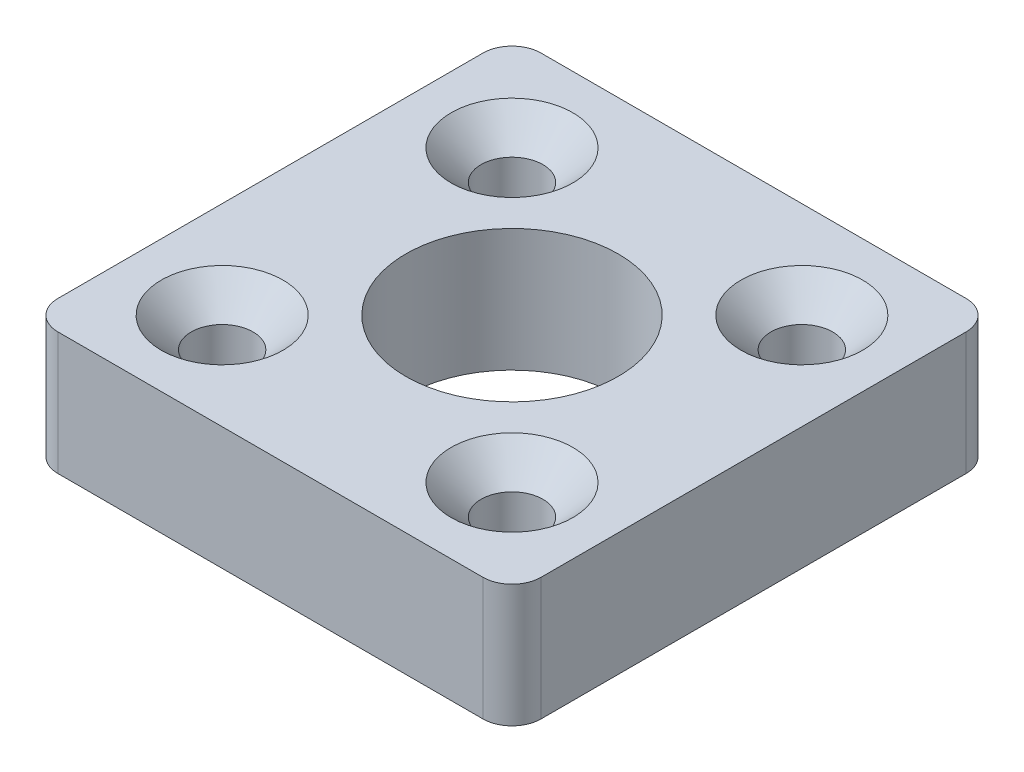
SolidWorks part; units mm, degrees
material "6061 Alloy"
ref_plane "Front Plane" through (0, 0, 0) normal (0, 0, 1) x (1, 0, 0)
ref_plane "Top Plane" through (0, 0, 0) normal (0, 1, 0) x (1, 0, 0)
ref_plane "Right Plane" through (0, 0, 0) normal (1, 0, 0) x (0, 0, -1)
sketch "Sketch2" plane through (0, 0, 0) normal (0, 1, 0) x (1, 0, 0)
  line L1 (-25, 25) -> (25, 25)
  line L2 (-25, 25) -> (-25, -25)
  line L3 (-25, -25) -> (25, -25)
  line L4 (25, 25) -> (25, -25)
  line L5 (-15, 15) -> (15, 15) construction
  line L6 (-15, 15) -> (-15, -15) construction
  line L7 (-15, -15) -> (15, -15) construction
  line L8 (15, 15) -> (15, -15) construction
  circle A0 centre (0, 0) radius 10.993
  circle A1 centre (-15, 15) radius 2.5 construction
  circle A2 centre (15, 15) radius 2.5 construction
  circle A3 centre (15, -15) radius 2.5 construction
  circle A4 centre (-15, -15) radius 2.5 construction
  point P4 (0, 25)
  point P6 (-25, 0)
  point P13 (0, 15)
  point P14 (-15, 0)
  dimension "D1" = 21.986
  dimension "D3" = 5
  dimension "D2" = 50
  dimension "D4" = 30
extrude "Boss-Extrude1" add sketch "Sketch2" against normal blind 12.7 contours L2 L3 L4 L1
hole_wizard "CSK for M6 Flat Head Machine Screw1" positions "3DSketch1" profile "Sketch3" countersink size "M6" standard "ANSI Metric" end condition through all
sketch3d "3DSketch1"
  point P0 (-15, 0, 15)
  point P2 (15, 0, 15)
  point P6 (-15, 0, -15)
  point P23 (15, 0, -15)
sketch "Sketch3" plane through (-15, 0, 15) normal (1, 0, 0) x (0, 0, 1)
  line L0 (0, 0) -> (0, 12.7)
  line L1 (0, 12.7) -> (3.2, 12.7)
  line L2 (3.2, 12.7) -> (3.2, 3.1)
  line L3 (3.2, 3.1) -> (6.3, 0)
  line L5 (6.3, 0) -> (0, 0)
  line L6 (-3.2, 3.1) -> (-6.3, 0) construction
  line L11 (0, -6.35) -> (0, 107.95) construction
  dimension "Thru Hole Dia." = 6.4
  dimension "Thru Hole Depth" = 12.7
  dimension "Near C'Sink Dia." = 12.6
  dimension "Near C'Sink Angle" = 90
fillet "Fillet1" radius 3 4 edges at (-25, -6.35, -25) (25, -6.35, -25) (25, -6.35, 25) (-25, -6.35, 25)
